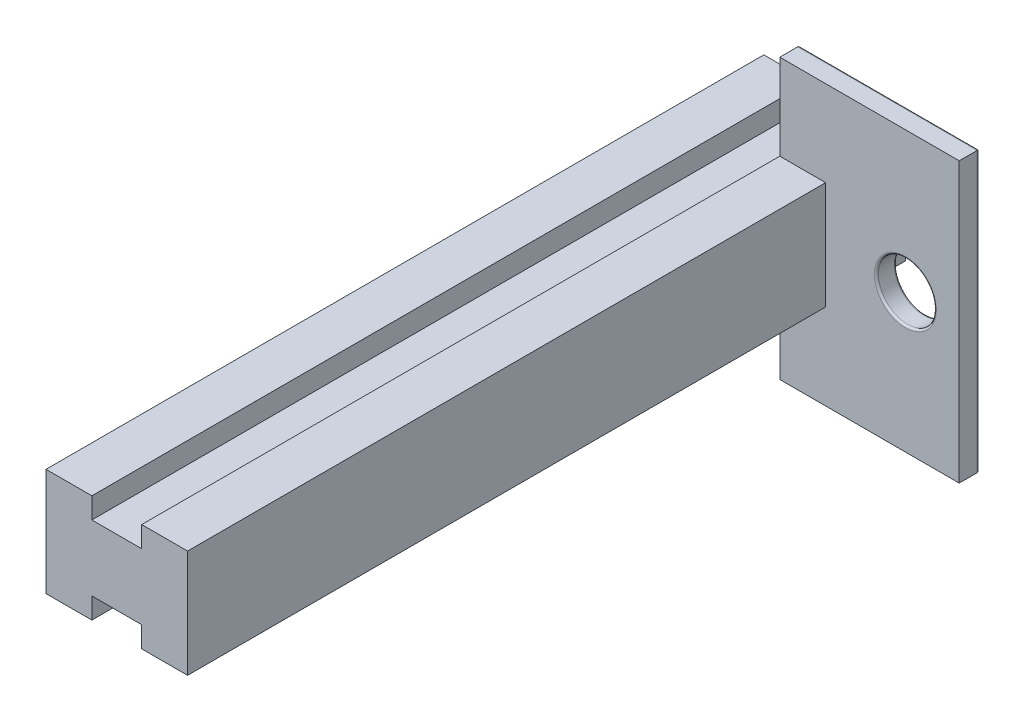
SolidWorks part; units mm, degrees
ref_plane "Front Plane" through (0, 0, 0) normal (0, 0, 1) x (1, 0, 0)
ref_plane "Top Plane" through (0, 0, 0) normal (0, 1, 0) x (1, 0, 0)
ref_plane "Right Plane" through (0, 0, 0) normal (1, 0, 0) x (0, 0, -1)
sketch "Sketch1" plane through (0, 0, 0) normal (0, 0, 1) x (1, 0, 0)
  line L8 (-1.3, 2.75) -> (-3.6, 2.75)
  line L9 (-1.3, 2.75) -> (-1.3, 1.7)
  line L10 (-1.3, -2.65) -> (-3.6, -2.65)
  line L11 (-3.6, 2.75) -> (-3.6, -2.65)
  line L14 (-1.3, -1.6) -> (-1.3, -2.65)
  line L15 (1.2, 2.75) -> (3.5, 2.75)
  line L16 (1.2, 2.75) -> (1.2, 1.7)
  line L17 (1.2, -2.65) -> (3.5, -2.65)
  line L18 (3.5, 2.75) -> (3.5, -2.65)
  line L21 (1.2, -1.6) -> (1.2, -2.65)
  line L22 (1.2, -1.6) -> (-1.3, -1.6)
  line L23 (1.2, 1.7) -> (-1.3, 1.7)
  point P0 (0, 0)
  dimension "D1" = 7.1
  dimension "D2" = 2.5
  dimension "D3" = 1.05
  dimension "D4" = 5.4
extrude "Boss-Extrude1" add sketch "Sketch1" along normal blind 60 contours L8 L11 L10 L14 L22 L21 L17 L18 L15 L16 L23 L9
sketch "Sketch2" plane through (0, 2.75, 0) normal (0, 1, 0) x (1, 0, 0)
  line L0 (2.35, 0) -> (2.35, -3) construction
  line L1 (1.2, 0) -> (3.5, 0) construction
  line L2 (1.2, -60) -> (1.2, 0) construction
  line L3 (1.2, -3) -> (3.5, -3)
  line L4 (3.5, -60) -> (3.5, 0) construction
  line L5 (3.5, -3) -> (3.5, -4)
  line L6 (3.5, -4) -> (1.2, -4)
  line L7 (1.2, -4) -> (1.2, -3)
  dimension "D1" = 3
  dimension "D2" = 1
extrude "Cut-Extrude1" cut sketch "Sketch2" against normal blind 10
sketch "Sketch3" plane through (1.2, 0, 0) normal (1, 0, 0) x (0, 0, -1)
  line L4 (0, 0) -> (-3, 0.05) construction
  line L5 (-3, -1.6) -> (-3, 1.7) construction
  line L6 (-3, 7.05) -> (-3, -6.95)
  line L7 (-3, -6.95) -> (-4, -6.95)
  line L8 (-4, -6.95) -> (-4, 7.05)
  line L9 (-4, 7.05) -> (-3, 7.05)
  point P9 (-3, 0.05)
  dimension "D1" = 1
  dimension "D2" = 14
extrude "Boss-Extrude2" add sketch "Sketch3" along normal blind 9
sketch "Sketch4" plane through (0, 0, 3) normal (0, 0, -1) x (-1, 0, 0)
  line L0 (0, 0) -> (-7.5, 0) construction
  circle A0 centre (-7.5, 0) radius 1.45
  dimension "D2" = 2.9
  dimension "D1" = 7.5
extrude "Cut-Extrude2" cut sketch "Sketch4" against normal blind 9
fillet "Fillet1" radius 0.1 12 edges at (1.2, -2.65, 1.5) (1.2, 2.75, 1.5) (3.5, 0.05, 3) (2.35, -2.65, 3) (5.7, -6.95, 3) (1.2, -4.8, 3) (2.35, 2.75, 3) (1.2, 4.9, 3) (5.7, 7.05, 3) (10.2, 0.05, 3) (6.05, 0, 4) (6.05, 0, 3)
sketch "Sketch5" plane through (0, 0, 60) normal (0, 0, 1) x (1, 0, 0)
  line L1 (3.5, 2.75) -> (-3.6, 2.75)
  line L2 (3.5, 2.75) -> (3.5, -2.65)
  line L3 (3.5, -2.65) -> (-3.6, -2.65)
  line L4 (-3.6, 2.75) -> (-3.6, -2.65)
extrude "Cut-Extrude3" cut sketch "Sketch5" against normal blind 24
